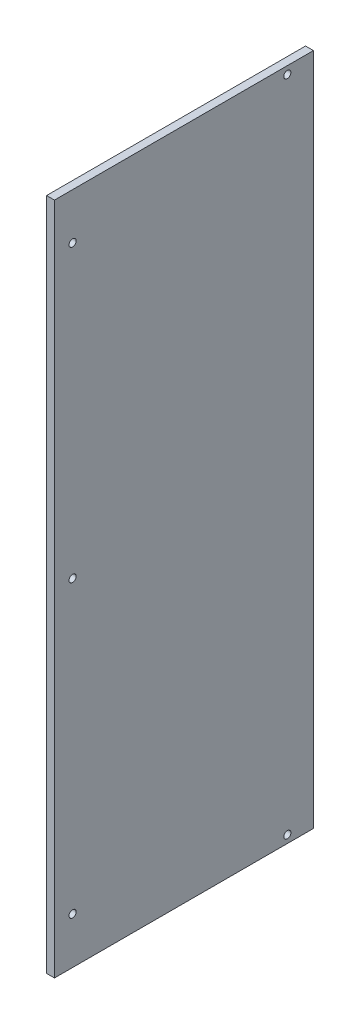
SolidWorks part; units mm, degrees
ref_plane "Front Plane" through (0, 0, 0) normal (0, 0, 1) x (1, 0, 0)
ref_plane "Top Plane" through (0, 0, 0) normal (0, 1, 0) x (1, 0, 0)
ref_plane "Right Plane" through (0, 0, 0) normal (1, 0, 0) x (0, 0, -1)
sketch "Sketch1" plane through (0, 0, 0) normal (1, 0, 0) x (0, 0, -1)
  line L1 (138.3478, 226.1644) -> (294.5578, 226.1644)
  line L2 (138.3478, 226.1644) -> (138.3478, -180.2356)
  line L3 (138.3478, -180.2356) -> (294.5578, -180.2356)
  line L4 (294.5578, 226.1644) -> (294.5578, -180.2356)
  dimension "D1" = 406.4
  dimension "D2" = 156.21
extrude "Boss-Extrude1" add sketch "Sketch1" along normal blind 4.7625
hole_wizard "#8 Clearance Hole1" positions "Sketch3" profile "Sketch4" hole size "#8" standard "ANSI Inch" end condition through all
sketch "Sketch3" plane through (0, 0, 0) normal (-1, 0, 0) x (0, 0, 1)
  point P0 (-149.2698, 198.3514)
  point P3 (-149.2698, -152.1686)
  point P7 (-149.2698, 23.0914)
  point P8 (-278.8098, 221.5289)
  point P11 (-278.8098, -175.6001)
sketch "Sketch4" plane through (0, 198.3514, -149.2698) normal (0, 1, 0) x (0, 0, 1)
  line L0 (0, 0) -> (0, 4.7625)
  line L1 (0, 4.7625) -> (2.1526, 4.7625)
  line L2 (2.1526, 4.7625) -> (2.1526, 0)
  line L5 (2.1526, 0) -> (0, 0)
  line L11 (0, -6.35) -> (0, 107.95) construction
  dimension "Thru Hole Dia." = 4.3053
  dimension "Thru Hole Depth" = 4.7625
